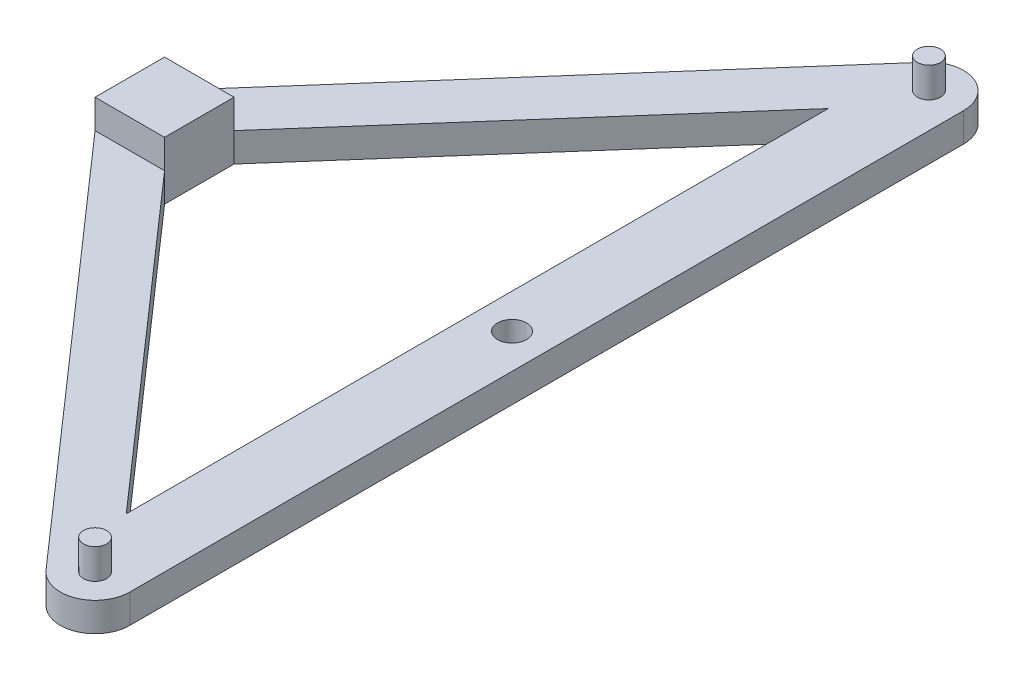
SolidWorks part; units mm, degrees
ref_plane "Front Plane" through (0, 0, 0) normal (0, 0, 1) x (1, 0, 0)
ref_plane "Top Plane" through (0, 0, 0) normal (0, 1, 0) x (1, 0, 0)
ref_plane "Right Plane" through (0, 0, 0) normal (1, 0, 0) x (0, 0, -1)
sketch "Sketch1" plane through (0, 0, 0) normal (0, 1, 0) x (1, 0, 0)
  line L1 (-3.81, 38.4871) -> (-3.81, -38.4871)
  line L2 (3.81, 45.72) -> (3.81, -45.72)
  line L4 (-41.91, 3.81) -> (-2.8617, 48.2353)
  line L5 (-41.91, -3.81) -> (-34.29, -3.81)
  line L6 (-41.91, -3.81) -> (-41.91, 3.81)
  line L7 (-41.91, 3.81) -> (-34.29, 3.81)
  line L8 (-34.29, -3.81) -> (-34.29, 3.81)
  line L9 (-41.91, -3.81) -> (-34.29, 3.81) construction
  line L10 (-41.91, 3.81) -> (-34.29, -3.81) construction
  line L11 (-34.29, 3.81) -> (-3.81, 38.4871)
  line L12 (-41.91, -3.81) -> (-2.8617, -48.2353)
  line L13 (-34.29, -3.81) -> (-3.81, -38.4871)
  arc A1 (-2.8617, -48.2353) -> (3.81, -45.72) centre (0, -45.72) ccw
  arc A2 (3.81, 45.72) -> (-2.8617, 48.2353) centre (0, 45.72) ccw
  point P4 (0, 0)
  dimension "D6" = 180
  dimension "D2" = 180
  dimension "D4" = 7.62
  dimension "D5" = 7.62
sketch "Sketch2" plane through (0, 0, 0) normal (0, 1, 0) x (1, 0, 0)
  line L0 (-3.81, 38.4871) -> (-3.81, -38.4871)
  line L1 (3.81, 45.72) -> (3.81, -45.72)
  line L2 (-41.91, 3.81) -> (-2.8617, 48.2353)
  line L3 (-41.91, -3.81) -> (-34.29, -3.81)
  line L4 (-41.91, -3.81) -> (-41.91, 3.81)
  line L5 (-41.91, 3.81) -> (-34.29, 3.81)
  line L6 (-34.29, -3.81) -> (-34.29, 3.81)
  line L7 (-34.29, 3.81) -> (-3.81, 38.4871)
  line L8 (-41.91, -3.81) -> (-2.8617, -48.2353)
  line L9 (-34.29, -3.81) -> (-3.81, -38.4871)
  arc A0 (-2.8617, -48.2353) -> (3.81, -45.72) centre (0, -45.72) ccw
  arc A1 (3.81, 45.72) -> (-2.8617, 48.2353) centre (0, 45.72) ccw
extrude "Boss-Extrude1" add sketch "Sketch2" along normal blind 3.175 contours L1 A1 L2 L5 L7 L0 L9 L3 L8 A0
sketch "Sketch3" plane through (0, 0, 0) normal (0, 1, 0) x (1, 0, 0)
  line L0 (-41.91, -3.81) -> (-34.29, -3.81)
  line L1 (-41.91, -3.81) -> (-41.91, 3.81)
  line L2 (-41.91, 3.81) -> (-34.29, 3.81)
  line L3 (-34.29, -3.81) -> (-34.29, 3.81)
extrude "Boss-Extrude2" add sketch "Sketch3" along normal blind 6.35
sketch "Sketch4" plane through (0, 3.175, 0) normal (0, 1, 0) x (1, 0, 0)
  circle A0 centre (0, 0) radius 1.5875
  circle A1 centre (0, 45.72) radius 1.27
  circle A2 centre (0, -45.72) radius 1.27
sketch "Sketch5" plane through (0, 3.175, 0) normal (0, 1, 0) x (1, 0, 0)
  circle A0 centre (0, 0) radius 1.5875
extrude "Cut-Extrude1" cut sketch "Sketch5" against normal up to surface (3.175 mm away) up to plane "Top Plane"
sketch "Sketch6" plane through (0, 3.175, 0) normal (0, 1, 0) x (1, 0, 0)
  circle A0 centre (0, 45.72) radius 1.27
  circle A1 centre (0, -45.72) radius 1.27
extrude "Boss-Extrude3" add sketch "Sketch6" along normal blind 3.302
sketch "Sketch7" plane through (-41.91, 0, 0) normal (-1, 0, 0) x (0, 0, 1)
  circle A0 centre (0, 3.175) radius 1.651
  point P9 (0, 3.175)
  dimension "D1" = 3.302
sketch "Sketch9" plane through (-41.91, 0, 0) normal (-1, 0, 0) x (0, 0, 1)
  circle A0 centre (0, 3.175) radius 1.651
extrude "Cut-Extrude3" cut sketch "Sketch9" against normal blind 3.175
